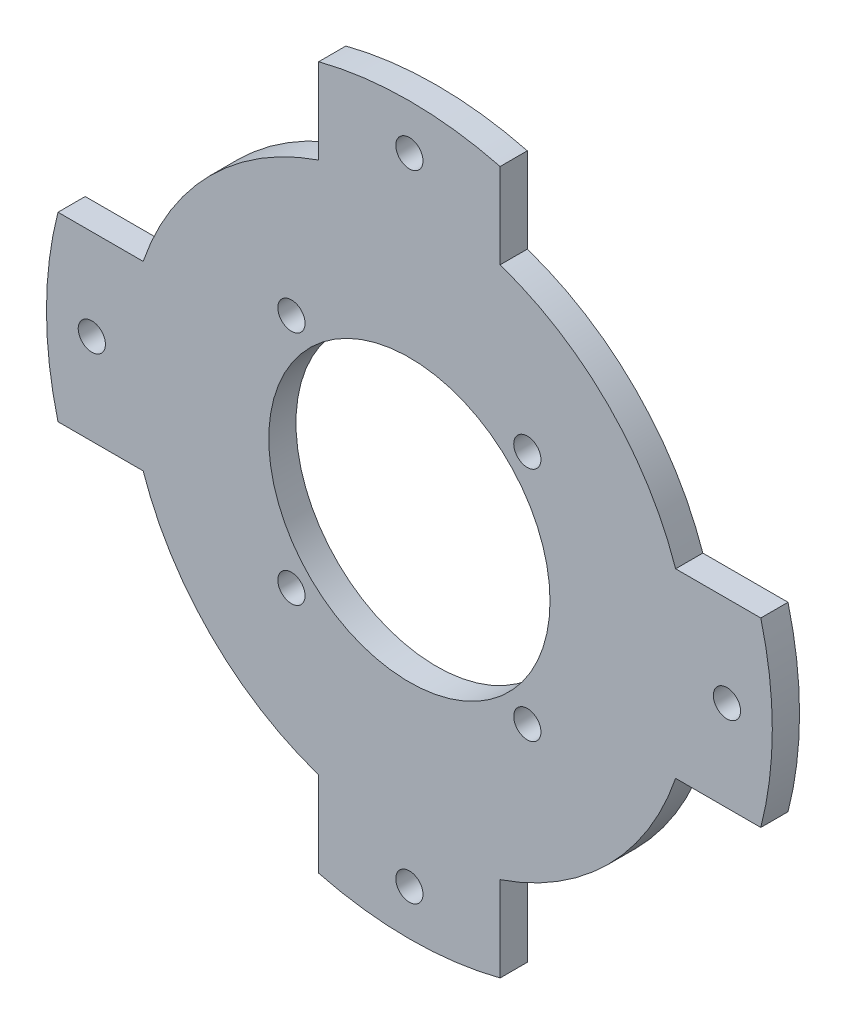
SolidWorks part; units mm, degrees
ref_plane "Front Plane" through (0, 0, 0) normal (0, 0, 1) x (1, 0, 0)
ref_plane "Top Plane" through (0, 0, 0) normal (0, 1, 0) x (1, 0, 0)
ref_plane "Right Plane" through (0, 0, 0) normal (1, 0, 0) x (0, 0, -1)
sketch "Sketch2" plane through (0, 0, 0) normal (0, 0, 1) x (1, 0, 0)
  line L10 (-10, -29.3428) -> (-10, -38.7298)
  line L11 (-29.3428, -10) -> (-38.7298, -10)
  line L16 (10, 29.3428) -> (10, 38.7298)
  line L18 (-10, 29.3428) -> (-10, 38.7298)
  line L19 (29.3428, 10) -> (38.7298, 10)
  line L20 (29.3428, -10) -> (38.7298, -10)
  line L21 (10, -29.3428) -> (10, -38.7298)
  line L22 (-29.3428, 10) -> (-38.7298, 10)
  arc A0 (-38.7298, 10) -> (-38.7298, -10) centre (0, 0) ccw
  arc A1 (-10, 29.3428) -> (-29.3428, 10) centre (0, 0) ccw
  arc A2 (10, 38.7298) -> (-10, 38.7298) centre (0, 0) ccw
  arc A3 (29.3428, 10) -> (10, 29.3428) centre (0, 0) ccw
  arc A4 (-10, -38.7298) -> (10, -38.7298) centre (0, 0) ccw
  arc A5 (-29.3428, -10) -> (-10, -29.3428) centre (0, 0) ccw
  arc A6 (38.7298, -10) -> (38.7298, 10) centre (0, 0) ccw
  arc A7 (10, -29.3428) -> (29.3428, -10) centre (0, 0) ccw
  point P24 (0, 0)
  dimension "D1" = 80
  dimension "D2" = 62
extrude "Boss-Extrude2" add sketch "Sketch2" along normal blind 3
sketch "Sketch3" plane through (0, 0, 3) normal (0, 0, 1) x (1, 0, 0)
  line L0 (0, 0) -> (0, 40) construction
  arc A0 (10, 38.7298) -> (-10, 38.7298) centre (0, 0) ccw construction
  circle A1 centre (0, 35) radius 1.5
  circle A2 centre (35, 0) radius 1.5
  circle A3 centre (0, -35) radius 1.5
  circle A4 centre (-35, 0) radius 1.5
  point P17 (0, 0)
  dimension "D1" = 35
  dimension "D2" = 3
extrude "Cut-Extrude1" cut sketch "Sketch3" against normal up to next
sketch "Sketch4" plane through (0, 0, 3) normal (0, 0, 1) x (1, 0, 0)
  line L0 (0, 0) -> (0, 40) construction
  line L1 (13, -13) -> (-13, -13) construction
  line L2 (13, -13) -> (13, 13) construction
  line L3 (13, 13) -> (-13, 13) construction
  line L4 (-13, -13) -> (-13, 13) construction
  line L5 (13, -13) -> (-13, 13) construction
  line L6 (13, 13) -> (-13, -13) construction
  line L7 (-21.5332, 0) -> (21.5332, 0) construction
  circle A0 centre (0, 0) radius 15.5
  arc A2 (10, 38.7298) -> (-10, 38.7298) centre (0, 0) ccw construction
  circle A3 centre (-13, 13) radius 1.5
  circle A4 centre (-13, -13) radius 1.5
  circle A5 centre (13, -13) radius 1.5
  circle A6 centre (13, 13) radius 1.5
  point P14 (0, 0)
  dimension "D1" = 31
  dimension "D4" = 3
  dimension "D2" = 26
  dimension "D3" = 26
extrude "Cut-Extrude2" cut sketch "Sketch4" against normal blind 3
